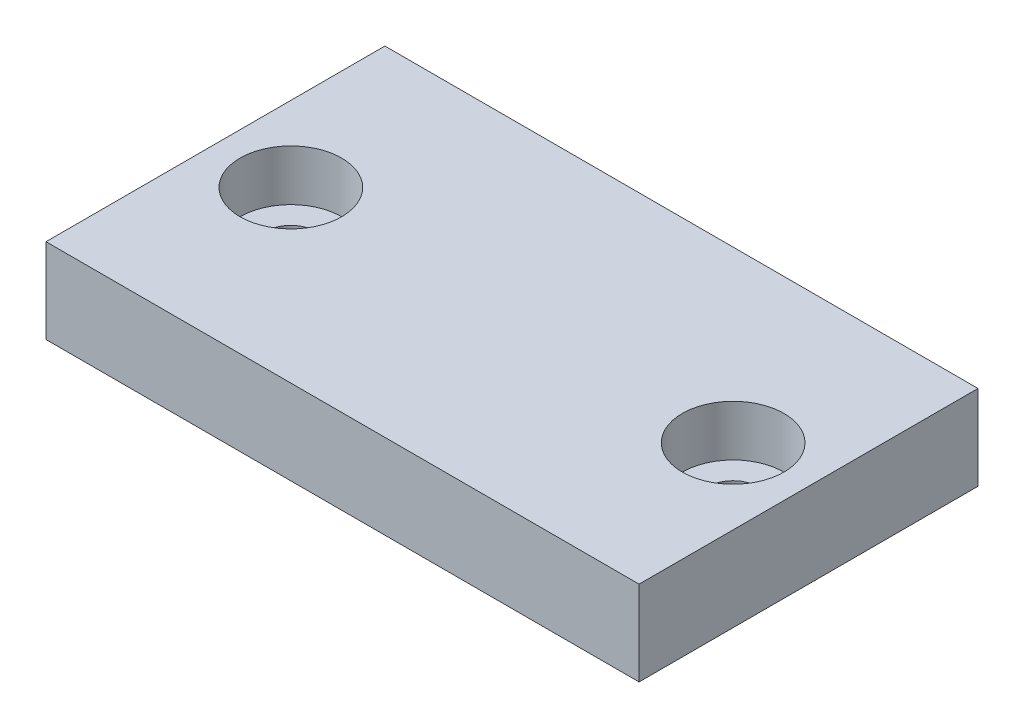
SolidWorks part; units mm, degrees
ref_plane "Front Plane" through (0, 0, 0) normal (0, 0, 1) x (1, 0, 0)
ref_plane "Top Plane" through (0, 0, 0) normal (0, 1, 0) x (1, 0, 0)
ref_plane "Right Plane" through (0, 0, 0) normal (1, 0, 0) x (0, 0, -1)
sketch "Sketch2" plane through (0, 0, 0) normal (0, 1, 0) x (1, 0, 0)
  line L0 (-13.05, 10) -> (-13.05, -10) construction
  line L1 (17.5, -10) -> (-17.5, -10)
  line L2 (17.5, -10) -> (17.5, 10)
  line L3 (17.5, 10) -> (-17.5, 10)
  line L4 (-17.5, -10) -> (-17.5, 10)
  line L5 (17.5, -10) -> (-17.5, 10) construction
  line L6 (17.5, 10) -> (-17.5, -10) construction
  line L7 (13.05, 10) -> (13.05, -10) construction
  line L8 (-13.05, 0) -> (13.05, 0) construction
  circle A0 centre (-13.05, 0) radius 1.5
  circle A1 centre (13.05, 0) radius 1.5
  point P0 (0, 0)
  point P14 (0, 0)
  dimension "D3" = 3
  dimension "D4" = 3
  dimension "D1" = 35
  dimension "D2" = 20
  dimension "D5" = 26.1
extrude "Boss-Extrude1" add sketch "Sketch2" along normal blind 5
sketch "Sketch3" plane through (0, 5, 0) normal (0, 1, 0) x (1, 0, 0)
  circle A0 centre (-13.05, 0) radius 3
  circle A1 centre (13.05, 0) radius 3
  dimension "D1" = 6
  dimension "D2" = 6
extrude "Cut-Extrude1" cut sketch "Sketch3" against normal blind 3
